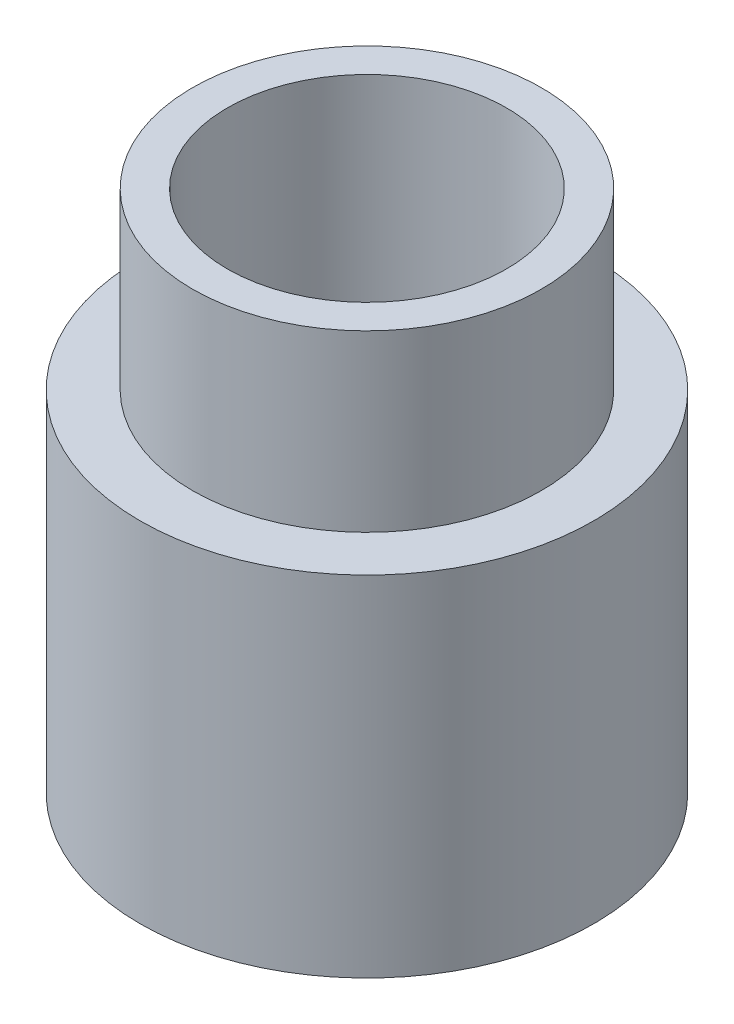
SolidWorks part; units mm, degrees
ref_plane "Front Plane" through (0, 0, 0) normal (0, 0, 1) x (1, 0, 0)
ref_plane "Top Plane" through (0, 0, 0) normal (0, 1, 0) x (1, 0, 0)
ref_plane "Right Plane" through (0, 0, 0) normal (1, 0, 0) x (0, 0, -1)
sketch "Sketch1" plane through (0, 0, 0) normal (0, 1, 0) x (1, 0, 0)
  circle A0 centre (0, 0) radius 6.5
  dimension "D1" = 13
extrude "Boss-Extrude1" add sketch "Sketch1" along normal blind 10
sketch "Sketch2" plane through (0, 10, 0) normal (0, 1, 0) x (1, 0, 0)
  circle A0 centre (0, 0) radius 5
  dimension "D1" = 10
extrude "Boss-Extrude2" add sketch "Sketch2" along normal blind 5
shell "Shell1" thickness 1
